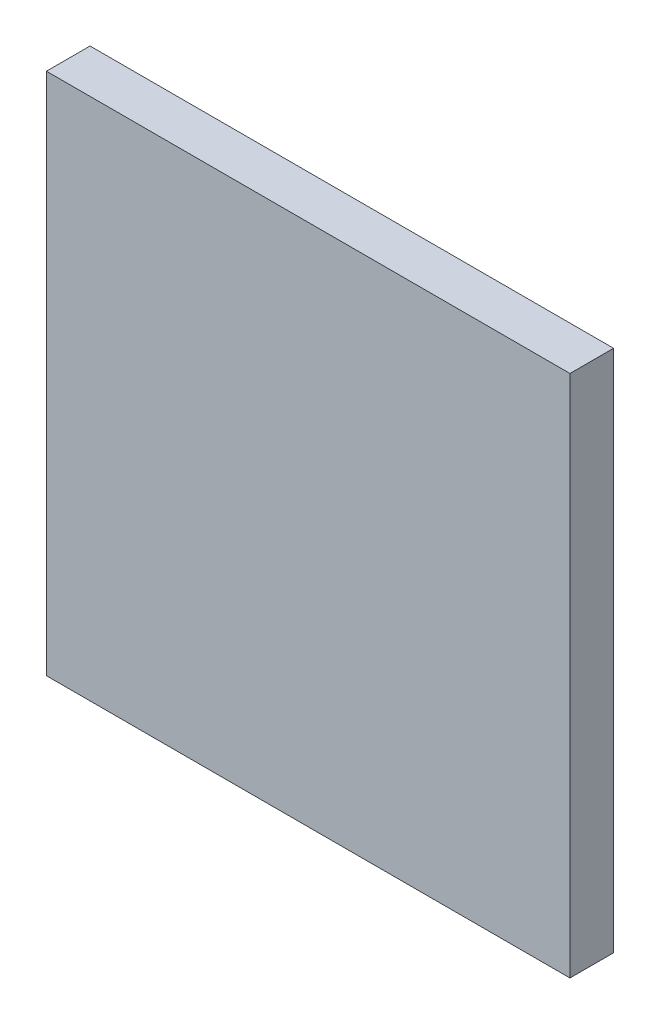
SolidWorks part; units mm, degrees
ref_plane "Front Plane" through (0, 0, 0) normal (0, 0, 1) x (1, 0, 0)
ref_plane "Top Plane" through (0, 0, 0) normal (0, 1, 0) x (1, 0, 0)
ref_plane "Right Plane" through (0, 0, 0) normal (1, 0, 0) x (0, 0, -1)
sketch "Sketch1" plane through (0, 0, 0) normal (0, 0, 1) x (1, 0, 0)
  line L1 (0, 0) -> (120000, 0)
  line L2 (0, 0) -> (0, 120000)
  line L3 (0, 120000) -> (120000, 120000)
  line L4 (120000, 0) -> (120000, 120000)
  dimension "D1" = 120000
  dimension "D2" = 120000
extrude "Boss-Extrude1" add sketch "Sketch1" along normal blind 10000
